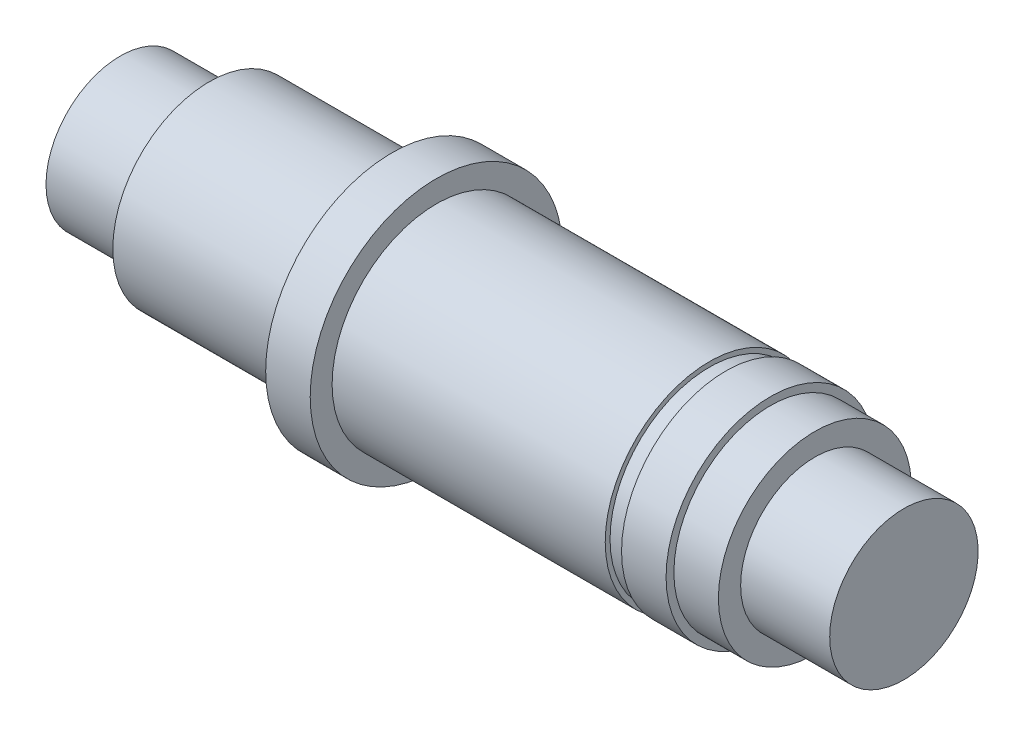
SolidWorks part; units mm, degrees
ref_plane "Front Plane" through (0, 0, 0) normal (0, 0, 1) x (1, 0, 0)
ref_plane "Top Plane" through (0, 0, 0) normal (0, 1, 0) x (1, 0, 0)
ref_plane "Right Plane" through (0, 0, 0) normal (1, 0, 0) x (0, 0, -1)
sketch "Sketch1" plane through (0, 0, 0) normal (0, 0, 1) x (1, 0, 0)
  line L0 (-13.6685, 0) -> (51.2825, 0) construction
  line L1 (0, 0) -> (0, 5)
  line L2 (0, 5) -> (6, 5)
  line L3 (6, 5) -> (6, 6.5)
  line L4 (6, 6.5) -> (18.3, 6.5)
  line L5 (18.3, 6.5) -> (18.3, 8.5)
  line L6 (18.3, 8.5) -> (21.3, 8.5)
  line L7 (21.3, 8.5) -> (21.3, 7.025)
  line L8 (21.3, 7.025) -> (39.7, 7.025)
  line L10 (46.8, 5) -> (52.8, 5)
  line L11 (52.8, 5) -> (52.8, 0)
  line L12 (0, 0) -> (52.8, 0)
  line L13 (39.7, 7.025) -> (39.7, 6.7)
  line L14 (39.7, 6.7) -> (40.8, 6.7)
  line L15 (40.8, 6.7) -> (40.8, 7.025)
  line L19 (40.8, 7.025) -> (43.8, 7.025)
  line L20 (43.8, 7.025) -> (43.8, 6.5)
  line L22 (43.8, 6.5) -> (46.8, 6.5)
  line L23 (46.8, 6.5) -> (46.8, 5)
  point P21 (0, 0)
  dimension "D1" = 5
  dimension "D2" = 6.5
  dimension "D3" = 12.3
  dimension "D4" = 6
  dimension "D5" = 3
  dimension "D6" = 6.5
  dimension "D7" = 7.025
  dimension "D8" = 3
  dimension "D9" = 3
  dimension "D10" = 2
  dimension "D11" = 6.7
  dimension "D12" = 1.1
  dimension "D13" = 21.4
revolve "Revolve1" add sketch "Sketch1" angle 360 about L0
